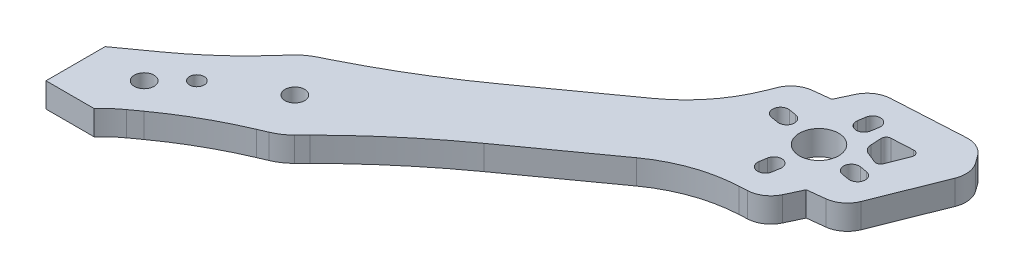
SolidWorks part; units mm, degrees
material "Thornel Mat VMA"
ref_plane "Front Plane" through (0, 0, 0) normal (0, 0, 1) x (1, 0, 0)
ref_plane "Top Plane" through (0, 0, 0) normal (0, 1, 0) x (1, 0, 0)
ref_plane "Right Plane" through (0, 0, 0) normal (1, 0, 0) x (0, 0, -1)
sketch "Sketch1" plane through (0, 0, 0) normal (0, 1, 0) x (1, 0, 0)
  line L0 (100.6189, 76.1698) -> (96.189, 75.9294)
  line L1 (95.2447, 74.8766) -> (95.3638, 72.6822)
  line L2 (96.6216, 70.9323) -> (98.6636, 70.1199)
  line L3 (99.9624, 70.6795) -> (101.6022, 74.8016)
  line L4 (0, 12.0488) -> (0, 0)
  line L5 (6.5997, 16.7923) -> (0, 12.0488)
  line L6 (20.403, 29.4979) -> (19.1123, 28.0515)
  line L7 (25.3723, 32.7718) -> (23.4012, 31.7888)
  line L8 (64.9914, 58.7613) -> (46.9317, 45.781)
  line L9 (75.6639, 73.2425) -> (75.0428, 71.6681)
  line L10 (83.3258, 76.7858) -> (79.7454, 76.3752)
  line L11 (84.8584, 80.0531) -> (83.3258, 76.7858)
  line L12 (103.8137, 83.732) -> (89.1102, 82.9223)
  line L13 (109.204, 80.1896) -> (108.1487, 81.6577)
  line L14 (104.3343, 61.741) -> (109.7883, 75.4195)
  line L15 (96.6742, 58.2142) -> (100.2596, 58.6254)
  line L16 (95.1438, 54.9514) -> (96.6742, 58.2142)
  line L17 (89.1833, 51.9944) -> (90.8736, 52.0813)
  line L18 (55.6863, 33.6007) -> (73.7459, 46.5811)
  line L19 (34.9238, 15.7573) -> (36.4839, 17.3123)
  line L20 (30.0144, 12.8833) -> (31.7968, 13.6457)
  line L21 (13.2935, 3.1309) -> (15.3543, 4.6121)
  line L22 (0, 0) -> (9.8274, 0)
  circle A0 centre (15.365, 15.365) radius 1.5
  circle A1 centre (88.4659, 58.1247) radius 1.5
  circle A2 centre (91.5341, 76.8753) radius 1.5
  circle A3 centre (27.8644, 22.84) radius 2
  circle A4 centre (10, 10) radius 2
  circle A5 centre (97.895, 66.2081) radius 1.5
  circle A6 centre (82.105, 68.7919) radius 1.5
  circle A7 centre (90, 67.5) radius 4
  arc A8 (101.6022, 74.8016) -> (100.6189, 76.1698) centre (100.6731, 75.1713) ccw
  arc A9 (96.189, 75.9294) -> (95.2447, 74.8766) centre (96.2432, 74.9308) ccw
  arc A10 (95.3638, 72.6822) -> (96.6216, 70.9323) centre (97.3609, 72.7906) ccw
  arc A11 (98.6636, 70.1199) -> (99.9624, 70.6795) centre (99.0332, 71.0491) ccw
  arc A12 (6.5997, 16.7923) -> (19.1123, 28.0515) centre (-38.3402, 79.3175) ccw
  arc A13 (23.4012, 31.7888) -> (20.403, 29.4979) centre (27.8644, 22.84) ccw
  arc A14 (25.3723, 32.7718) -> (46.9317, 45.781) centre (-44.6991, 173.2674) ccw
  arc A15 (64.9914, 58.7613) -> (75.0428, 71.6681) centre (48.0659, 82.3098) ccw
  arc A16 (79.7454, 76.3752) -> (75.6639, 73.2425) centre (80.3151, 71.4078) ccw
  arc A17 (89.1102, 82.9223) -> (84.8584, 80.0531) centre (89.3851, 77.9298) ccw
  arc A18 (108.1487, 81.6577) -> (103.8137, 83.732) centre (104.0887, 78.7395) ccw
  arc A19 (109.7883, 75.4195) -> (109.204, 80.1896) centre (105.1439, 77.2714) ccw
  arc A20 (100.2596, 58.6254) -> (104.3343, 61.741) centre (99.6898, 63.5928) ccw
  arc A21 (90.8736, 52.0813) -> (95.1438, 54.9514) centre (90.617, 57.0747) ccw
  arc A22 (89.1833, 51.9944) -> (73.7459, 46.5811) centre (90.6714, 23.0326) ccw
  arc A23 (55.6863, 33.6007) -> (36.4839, 17.3123) centre (147.3171, -93.8857) ccw
  arc A24 (31.7968, 13.6457) -> (34.9238, 15.7573) centre (27.8644, 22.84) ccw
  arc A25 (30.0144, 12.8833) -> (15.3543, 4.6121) centre (60.2943, -57.9131) ccw
  arc A26 (13.2935, 3.1309) -> (9.8274, 0) centre (25.5498, -13.9214) ccw
sketch "Sketch2" plane through (0, 0, 0) normal (0, 1, 0) x (1, 0, 0)
  line L0 (108.6764, 80.9236) -> (27.8644, 22.84) construction
  line L1 (90, 67.5) -> (88.4659, 58.1247) construction
  line L2 (90, 67.5) -> (91.5341, 76.8753) construction
  line L4 (100.6189, 76.1698) -> (96.189, 75.9294)
  line L5 (95.2447, 74.8766) -> (95.3638, 72.6822)
  line L6 (96.6216, 70.9323) -> (98.6636, 70.1199)
  line L7 (99.9624, 70.6795) -> (101.6022, 74.8016)
  line L8 (100.6189, 76.1698) -> (96.189, 75.9294)
  line L9 (95.2447, 74.8766) -> (95.3638, 72.6822)
  line L10 (96.6216, 70.9323) -> (98.6636, 70.1199)
  line L11 (99.9624, 70.6795) -> (101.6022, 74.8016)
  line L13 (90, 67.5) -> (99.3753, 65.9659) construction
  line L16 (90, 67.5) -> (80.6247, 69.0341) construction
  line L19 (90.131, 76.3449) -> (92.695, 75.9254) construction
  line L22 (83.3258, 76.7858) -> (96.6742, 58.2142) construction
  line L23 (81.1551, 67.631) -> (81.5746, 70.195) construction
  line L24 (87.305, 59.0746) -> (89.869, 58.6551) construction
  line L25 (98.8449, 67.369) -> (98.4254, 64.805) construction
  line L26 (99.3753, 65.9659) -> (97.895, 66.2081) construction
  line L27 (96.6742, 58.2142) -> (100.2596, 58.6254)
  line L28 (95.1438, 54.9514) -> (96.6742, 58.2142)
  line L29 (89.1833, 51.9944) -> (90.8736, 52.0813)
  line L30 (55.6863, 33.6007) -> (73.7459, 46.5811)
  line L31 (34.9238, 15.7573) -> (36.4839, 17.3123)
  line L32 (30.0144, 12.8833) -> (31.7968, 13.6457)
  line L33 (13.2935, 3.1309) -> (15.3543, 4.6121)
  line L34 (0, 0) -> (9.8274, 0)
  line L35 (0, 12.0488) -> (0, 0)
  line L36 (6.5997, 16.7923) -> (0, 12.0488)
  line L37 (20.403, 29.4979) -> (19.1123, 28.0515)
  line L38 (25.3723, 32.7718) -> (23.4012, 31.7888)
  line L39 (64.9914, 58.7613) -> (46.9317, 45.781)
  line L40 (75.6639, 73.2425) -> (75.0428, 71.6681)
  line L41 (83.3258, 76.7858) -> (79.7454, 76.3752)
  line L42 (84.8584, 80.0531) -> (83.3258, 76.7858)
  line L43 (103.8137, 83.732) -> (89.1102, 82.9223)
  line L44 (109.204, 80.1896) -> (108.1487, 81.6577)
  line L45 (104.3343, 61.741) -> (109.7883, 75.4195)
  line L46 (96.6742, 58.2142) -> (100.2596, 58.6254)
  line L47 (95.1438, 54.9514) -> (96.6742, 58.2142)
  line L48 (89.1833, 51.9944) -> (90.8736, 52.0813)
  line L49 (55.6863, 33.6007) -> (73.7459, 46.5811)
  line L50 (34.9238, 15.7573) -> (36.4839, 17.3123)
  line L51 (30.0144, 12.8833) -> (31.7968, 13.6457)
  line L52 (13.2935, 3.1309) -> (15.3543, 4.6121)
  line L53 (0, 0) -> (9.8274, 0)
  line L54 (0, 12.0488) -> (0, 0)
  line L55 (6.5997, 16.7923) -> (0, 12.0488)
  line L56 (20.403, 29.4979) -> (19.1123, 28.0515)
  line L57 (25.3723, 32.7718) -> (23.4012, 31.7888)
  line L58 (64.9914, 58.7613) -> (46.9317, 45.781)
  line L59 (75.6639, 73.2425) -> (75.0428, 71.6681)
  line L60 (83.3258, 76.7858) -> (79.7454, 76.3752)
  line L61 (84.8584, 80.0531) -> (83.3258, 76.7858)
  line L62 (103.8137, 83.732) -> (89.1102, 82.9223)
  line L63 (109.204, 80.1896) -> (108.1487, 81.6577)
  line L64 (104.3343, 61.741) -> (109.7883, 75.4195)
  line L65 (99.1169, 64.3869) -> (97.6366, 64.6291)
  line L66 (99.6337, 67.5449) -> (98.1534, 67.7871)
  line L67 (91.5341, 76.8753) -> (91.2919, 75.395) construction
  line L68 (93.1131, 76.6169) -> (92.8709, 75.1366)
  line L69 (89.9551, 77.1337) -> (89.7129, 75.6534)
  line L70 (80.6247, 69.0341) -> (82.105, 68.7919) construction
  line L71 (80.3663, 67.4551) -> (81.8466, 67.2129)
  line L72 (80.8831, 70.6131) -> (82.3634, 70.3709)
  line L73 (88.4659, 58.1247) -> (88.7081, 59.605) construction
  line L74 (90.0449, 57.8663) -> (90.2871, 59.3466)
  line L75 (86.8869, 58.3831) -> (87.1291, 59.8634)
  circle A3 centre (10, 10) radius 2
  circle A4 centre (10, 10) radius 2
  circle A5 centre (27.8644, 22.84) radius 2
  circle A6 centre (27.8644, 22.84) radius 2
  circle A11 centre (15.365, 15.365) radius 1.5
  circle A12 centre (15.365, 15.365) radius 1.5
  circle A13 centre (90, 67.5) radius 4
  circle A14 centre (90, 67.5) radius 4
  arc A20 (96.189, 75.9294) -> (95.2447, 74.8766) centre (96.2432, 74.9308) ccw
  arc A21 (95.3638, 72.6822) -> (96.6216, 70.9323) centre (97.3609, 72.7906) ccw
  arc A22 (98.6636, 70.1199) -> (99.9624, 70.6795) centre (99.0332, 71.0491) ccw
  arc A23 (101.6022, 74.8016) -> (100.6189, 76.1698) centre (100.6731, 75.1713) ccw
  arc A24 (96.189, 75.9294) -> (95.2447, 74.8766) centre (96.2432, 74.9308) ccw
  arc A25 (95.3638, 72.6822) -> (96.6216, 70.9323) centre (97.3609, 72.7906) ccw
  arc A26 (98.6636, 70.1199) -> (99.9624, 70.6795) centre (99.0332, 71.0491) ccw
  arc A27 (101.6022, 74.8016) -> (100.6189, 76.1698) centre (100.6731, 75.1713) ccw
  circle A31 centre (90, 67.5) radius 8 construction
  circle A32 centre (90, 67.5) radius 9.5 construction
  arc A34 (81.5746, 70.195) -> (81.1551, 67.631) centre (80.6247, 69.0341) ccw construction
  arc A35 (81.1551, 67.631) -> (81.5746, 70.195) centre (82.105, 68.7919) ccw construction
  arc A36 (89.869, 58.6551) -> (87.305, 59.0746) centre (88.4659, 58.1247) cw construction
  arc A37 (87.305, 59.0746) -> (89.869, 58.6551) centre (88.7081, 59.605) cw construction
  arc A38 (98.8449, 67.369) -> (98.4254, 64.805) centre (97.895, 66.2081) ccw construction
  arc A39 (90.8736, 52.0813) -> (95.1438, 54.9514) centre (90.617, 57.0747) ccw
  arc A40 (89.1833, 51.9944) -> (73.7459, 46.5811) centre (90.6714, 23.0326) ccw
  arc A41 (55.6863, 33.6007) -> (36.4839, 17.3123) centre (147.3171, -93.8857) ccw
  arc A42 (31.7968, 13.6457) -> (34.9238, 15.7573) centre (27.8644, 22.84) ccw
  arc A43 (30.0144, 12.8833) -> (15.3543, 4.6121) centre (60.2943, -57.9131) ccw
  arc A44 (13.2935, 3.1309) -> (9.8274, 0) centre (25.5498, -13.9214) ccw
  arc A45 (6.5997, 16.7923) -> (19.1123, 28.0515) centre (-38.3402, 79.3175) ccw
  arc A46 (23.4012, 31.7888) -> (20.403, 29.4979) centre (27.8644, 22.84) ccw
  arc A47 (25.3723, 32.7718) -> (46.9317, 45.781) centre (-44.6991, 173.2674) ccw
  arc A48 (64.9914, 58.7613) -> (75.0428, 71.6681) centre (48.0659, 82.3098) ccw
  arc A49 (79.7454, 76.3752) -> (75.6639, 73.2425) centre (80.3151, 71.4078) ccw
  arc A50 (89.1102, 82.9223) -> (84.8584, 80.0531) centre (89.3851, 77.9298) ccw
  arc A51 (108.1487, 81.6577) -> (103.8137, 83.732) centre (104.0887, 78.7395) ccw
  arc A52 (109.7883, 75.4195) -> (109.204, 80.1896) centre (105.1439, 77.2714) ccw
  arc A53 (100.2596, 58.6254) -> (104.3343, 61.741) centre (99.6898, 63.5928) ccw
  arc A54 (90.8736, 52.0813) -> (95.1438, 54.9514) centre (90.617, 57.0747) ccw
  arc A55 (89.1833, 51.9944) -> (73.7459, 46.5811) centre (90.6714, 23.0326) ccw
  arc A56 (55.6863, 33.6007) -> (36.4839, 17.3123) centre (147.3171, -93.8857) ccw
  arc A57 (31.7968, 13.6457) -> (34.9238, 15.7573) centre (27.8644, 22.84) ccw
  arc A58 (30.0144, 12.8833) -> (15.3543, 4.6121) centre (60.2943, -57.9131) ccw
  arc A59 (13.2935, 3.1309) -> (9.8274, 0) centre (25.5498, -13.9214) ccw
  arc A60 (6.5997, 16.7923) -> (19.1123, 28.0515) centre (-38.3402, 79.3175) ccw
  arc A61 (23.4012, 31.7888) -> (20.403, 29.4979) centre (27.8644, 22.84) ccw
  arc A62 (25.3723, 32.7718) -> (46.9317, 45.781) centre (-44.6991, 173.2674) ccw
  arc A63 (64.9914, 58.7613) -> (75.0428, 71.6681) centre (48.0659, 82.3098) ccw
  arc A64 (79.7454, 76.3752) -> (75.6639, 73.2425) centre (80.3151, 71.4078) ccw
  arc A65 (89.1102, 82.9223) -> (84.8584, 80.0531) centre (89.3851, 77.9298) ccw
  arc A66 (108.1487, 81.6577) -> (103.8137, 83.732) centre (104.0887, 78.7395) ccw
  arc A67 (109.7883, 75.4195) -> (109.204, 80.1896) centre (105.1439, 77.2714) ccw
  arc A68 (100.2596, 58.6254) -> (104.3343, 61.741) centre (99.6898, 63.5928) ccw
  arc A69 (98.4254, 64.805) -> (98.8449, 67.369) centre (99.3753, 65.9659) ccw construction
  arc A70 (90.131, 76.3449) -> (92.695, 75.9254) centre (91.5341, 76.8753) cw construction
  arc A71 (92.695, 75.9254) -> (90.131, 76.3449) centre (91.2919, 75.395) cw construction
  arc A72 (99.1169, 64.3869) -> (99.6337, 67.5449) centre (99.3753, 65.9659) ccw
  arc A73 (98.1534, 67.7871) -> (97.6366, 64.6291) centre (97.895, 66.2081) ccw
  arc A74 (93.1131, 76.6169) -> (89.9551, 77.1337) centre (91.5341, 76.8753) ccw
  arc A75 (89.7129, 75.6534) -> (92.8709, 75.1366) centre (91.2919, 75.395) ccw
  arc A76 (80.3663, 67.4551) -> (80.8831, 70.6131) centre (80.6247, 69.0341) cw
  arc A77 (82.3634, 70.3709) -> (81.8466, 67.2129) centre (82.105, 68.7919) cw
  arc A78 (90.0449, 57.8663) -> (86.8869, 58.3831) centre (88.4659, 58.1247) cw
  arc A79 (87.1291, 59.8634) -> (90.2871, 59.3466) centre (88.7081, 59.605) cw
  point P23 (98.6352, 66.087)
  point P84 (91.413, 76.1352)
  point P93 (81.3648, 68.913)
  point P101 (88.587, 58.8648)
  dimension "D4" = 19
  dimension "D5" = 16
  dimension "D12" = 3
  dimension "D13" = 3
  dimension "D11" = 3.2
  dimension "D14" = 3.2
  dimension "D2" = 0
  dimension "D3" = 0
  dimension "D6" = 0
  dimension "D7" = 0
  dimension "D9" = 0
  dimension "D10" = 0
extrude "Boss-Extrude1" add sketch "Sketch2" along normal blind 5
